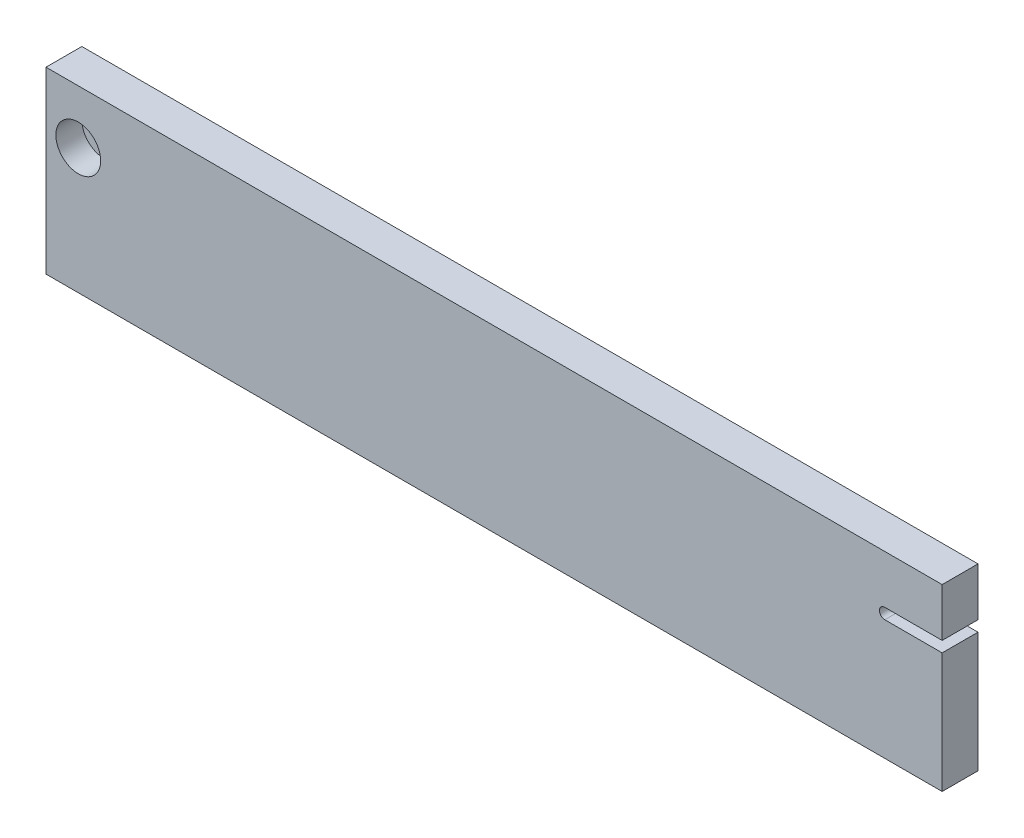
SolidWorks part; units mm, degrees
ref_plane "Front Plane" through (0, 0, 0) normal (0, 0, 1) x (1, 0, 0)
ref_plane "Top Plane" through (0, 0, 0) normal (0, 1, 0) x (1, 0, 0)
ref_plane "Right Plane" through (0, 0, 0) normal (1, 0, 0) x (0, 0, -1)
sketch "Sketch1" plane through (0, 0, 0) normal (0, 0, 1) x (1, 0, 0)
  line L1 (0, 0) -> (500, 0)
  line L2 (0, 0) -> (0, 100)
  line L3 (0, 100) -> (500, 100)
  line L4 (500, 0) -> (500, 100)
  dimension "D1" = 100
  dimension "D2" = 500
extrude "Boss-Extrude1" add sketch "Sketch1" along normal blind 20
sketch "Sketch2" plane through (0, 0, 20) normal (0, 0, 1) x (1, 0, 0)
  line L0 (468, 70) -> (520, 70) construction
  line L1 (468, 73) -> (520, 73)
  line L2 (468, 67) -> (520, 67)
  line L4 (500, 100) -> (0, 100) construction
  line L5 (500, 0) -> (500, 100) construction
  line L6 (0, 100) -> (0, 0) construction
  arc A0 (468, 73) -> (468, 67) centre (468, 70) ccw
  arc A1 (520, 67) -> (520, 73) centre (520, 70) ccw
  circle A2 centre (18, 70) radius 3
  point P2 (494, 70)
  dimension "D3" = 6
  dimension "D1" = 20
  dimension "D2" = 6
  dimension "D4" = 30
  dimension "D5" = 30
  dimension "D6" = 18
  dimension "D7" = 450
extrude "Cut-Extrude1" cut sketch "Sketch2" against normal through all
sketch "Sketch3" plane through (0, 0, 20) normal (0, 0, 1) x (1, 0, 0)
  circle A0 centre (18, 70) radius 12.5
  dimension "D1" = 25
extrude "Cut-Extrude2" cut sketch "Sketch3" against normal blind 14.5
sketch "Sketch4" plane through (0, 0, 5.5) normal (0, 0, 1) x (1, 0, 0)
  circle A0 centre (18, 70) radius 3.5
  dimension "D1" = 7
extrude "Cut-Extrude3" cut sketch "Sketch4" against normal blind 2.6
sketch "Sketch5" plane through (0, 0, 5.5) normal (0, 0, 1) x (1, 0, 0)
  circle A0 centre (18, 70) radius 8.5 construction
  circle A1 centre (18, 61.5) radius 1.5
  circle A2 centre (18, 78.5) radius 1.5
  dimension "D1" = 17
  dimension "D2" = 3
extrude "Cut-Extrude4" cut sketch "Sketch5" against normal through all
